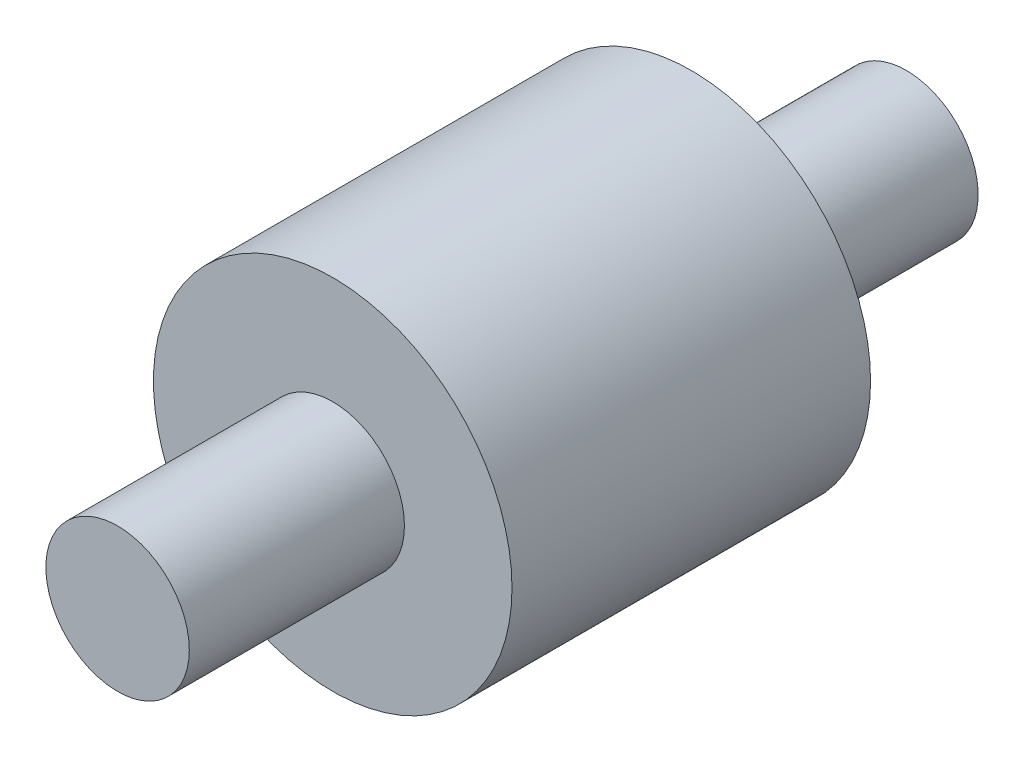
SolidWorks part; units mm, degrees
ref_plane "Front Plane" through (0, 0, 0) normal (0, 0, 1) x (1, 0, 0)
ref_plane "Top Plane" through (0, 0, 0) normal (0, 1, 0) x (1, 0, 0)
ref_plane "Right Plane" through (0, 0, 0) normal (1, 0, 0) x (0, 0, -1)
sketch "Sketch1" plane through (0, 0, 0) normal (0, 0, 1) x (1, 0, 0)
  circle A0 centre (0, 0) radius 25
  dimension "D1" = 50
extrude "Boss-Extrude1" add sketch "Sketch1" along normal mid plane 50
sketch "Sketch2" plane through (0, 0, -25) normal (0, 0, -1) x (-1, 0, 0)
  circle A0 centre (0, 0) radius 10
  dimension "D1" = 20
extrude "Boss-Extrude2" add sketch "Sketch2" along normal blind 30
sketch "Sketch3" plane through (0, 0, 25) normal (0, 0, 1) x (1, 0, 0)
  circle A0 centre (0, 0) radius 10
  dimension "D1" = 20
extrude "Boss-Extrude3" add sketch "Sketch3" along normal blind 30
